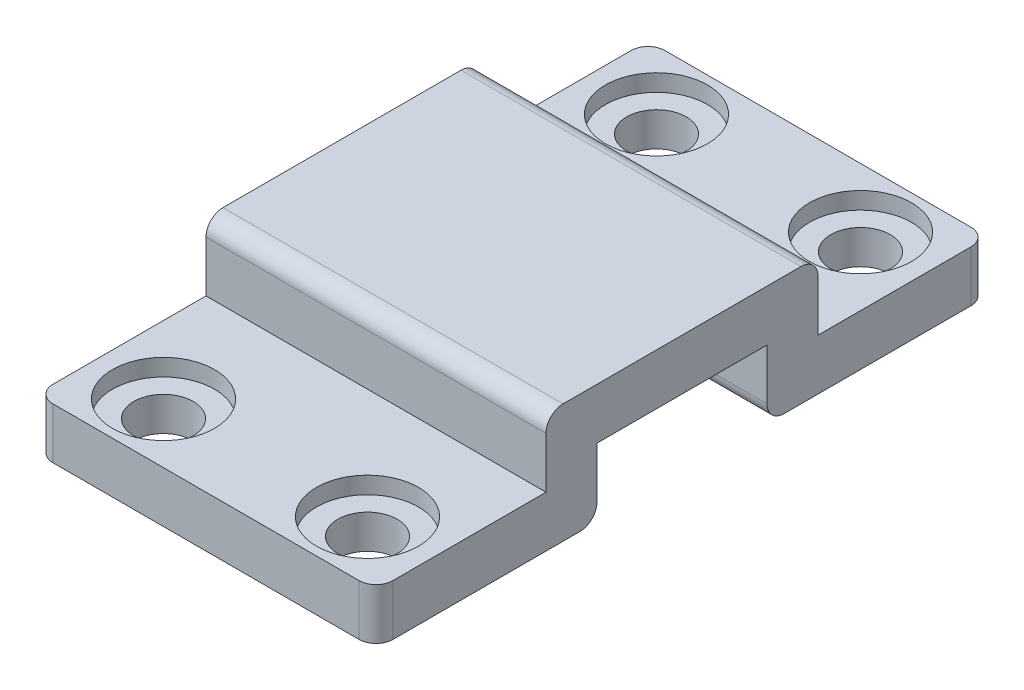
SolidWorks part; units mm, degrees
ref_plane "前视基准面" through (0, 0, 0) normal (0, 0, 1) x (1, 0, 0)
ref_plane "上视基准面" through (0, 0, 0) normal (0, 1, 0) x (1, 0, 0)
ref_plane "右视基准面" through (0, 0, 0) normal (1, 0, 0) x (0, 0, -1)
sketch "草图21" plane through (0, 0, 0) normal (0, 1, 0) x (1, 0, 0)
  line L1 (-10, -5) -> (10, -5)
  line L2 (-10, -5) -> (-10, 5)
  line L3 (-10, 5) -> (10, 5)
  line L4 (10, -5) -> (10, 5)
  line L5 (-10, -5) -> (10, 5) construction
  line L6 (-10, 5) -> (10, -5) construction
  point P0 (0, 0)
  dimension "D1" = 20
  dimension "D2" = 10
extrude "凸台-拉伸3" add sketch "草图21" along normal blind 3
sketch "草图22" plane through (0, 3, 0) normal (0, 1, 0) x (1, 0, 0)
  line L0 (-10, 0) -> (10, 0) construction
  line L1 (-10, -8) -> (10, -8)
  line L2 (-10, -8) -> (-10, -5)
  line L3 (-10, -5) -> (10, -5)
  line L4 (10, -8) -> (10, -5)
  line L5 (-10, -8) -> (10, -5) construction
  line L6 (-10, -5) -> (10, -8) construction
  line L7 (-10, 5) -> (-10, -5) construction
  line L8 (10, -5) -> (10, 5) construction
  line L9 (-10, 5) -> (10, 8) construction
  line L10 (-10, 8) -> (10, 5) construction
  line L11 (10, 8) -> (10, 5)
  line L12 (-10, 5) -> (10, 5)
  line L13 (-10, 8) -> (-10, 5)
  line L14 (-10, 8) -> (10, 8)
  point P0 (0, -6.5)
  point P16 (0, 6.5)
  dimension "D1" = 3
extrude "凸台-拉伸4" add sketch "草图22" against normal blind 7
sketch "草图23" plane through (0, 0, 8) normal (0, 0, 1) x (1, 0, 0)
  line L1 (-10, -1) -> (10, -1)
  line L2 (-10, -1) -> (-10, -4)
  line L3 (-10, -4) -> (10, -4)
  line L4 (10, -1) -> (10, -4)
  line L5 (-10, -1) -> (10, -4) construction
  line L6 (-10, -4) -> (10, -1) construction
  point P0 (0, -2.5)
  dimension "D1" = 3
extrude "凸台-拉伸5" add sketch "草图23" along normal blind 10
sketch "草图24" plane through (0, 0, -8) normal (0, 0, -1) x (-1, 0, 0)
  line L1 (-10, -1) -> (10, -1)
  line L2 (-10, -1) -> (-10, -4)
  line L3 (-10, -4) -> (10, -4)
  line L4 (10, -1) -> (10, -4)
  line L5 (-10, -1) -> (10, -4) construction
  line L6 (-10, -4) -> (10, -1) construction
  point P0 (0, -2.5)
  dimension "D1" = 3
extrude "凸台-拉伸6" add sketch "草图24" along normal blind 10
sketch "草图25" plane through (0, -1, 0) normal (0, 1, 0) x (1, 0, 0)
  line L0 (-10, 11) -> (10, 11) construction
  line L1 (-10, 18) -> (-10, 8) construction
  line L2 (10, 18) -> (10, 8) construction
  line L3 (10, 8) -> (-10, 8) construction
  line L4 (-10, 18) -> (-10, 11) construction
  line L5 (-10, 14.5) -> (10, 14.5) construction
  line L6 (0, 18) -> (0, -18) construction
  line L7 (-10, 18) -> (10, 18) construction
  line L8 (10, -18) -> (-10, -18) construction
  line L9 (-10, 0) -> (10, 0) construction
  line L10 (-10, 8) -> (-10, -8) construction
  line L11 (10, -8) -> (10, 8) construction
  circle A0 centre (-6, 14.5) radius 1.75
  circle A1 centre (-6, 14.5) radius 3
  circle A2 centre (6, 14.5) radius 3
  circle A3 centre (6, 14.5) radius 1.75
  circle A4 centre (6, -14.5) radius 1.75
  circle A5 centre (6, -14.5) radius 3
  circle A6 centre (-6, -14.5) radius 3
  circle A7 centre (-6, -14.5) radius 1.75
  dimension "D2" = 3.5
  dimension "D3" = 6
  dimension "D1" = 3
  dimension "D4" = 4
extrude "切除-拉伸1" cut sketch "草图25" against normal through all contours A0 | A3 | A7 | A4
sketch "草图26" plane through (0, -1, 0) normal (0, 1, 0) x (1, 0, 0)
  circle A1 centre (-6, 14.5) radius 3
  circle A2 centre (-6, 14.5) radius 3
  circle A3 centre (-6, 14.5) radius 1.75
  circle A4 centre (-6, 14.5) radius 1.75
  circle A5 centre (6, -14.5) radius 1.75
  circle A6 centre (6, -14.5) radius 1.75
  circle A7 centre (6, 14.5) radius 1.75
  circle A8 centre (6, 14.5) radius 1.75
  circle A9 centre (6, 14.5) radius 3
  circle A10 centre (6, 14.5) radius 3
  circle A11 centre (-6, -14.5) radius 1.75
  circle A12 centre (-6, -14.5) radius 1.75
  circle A13 centre (-6, -14.5) radius 3
  circle A14 centre (-6, -14.5) radius 3
  circle A15 centre (6, -14.5) radius 3
  circle A16 centre (6, -14.5) radius 3
  circle M13 centre (-6, 14.5) radius 1.75
  circle M14 centre (6, 14.5) radius 1.75
  dimension "D1" = 0
  dimension "D2" = 0
  dimension "D3" = 0
  dimension "D4" = 0
  dimension "D5" = 0
  dimension "D6" = 0
  dimension "D7" = 0
  dimension "D8" = 0
extrude "切除-拉伸2" cut sketch "草图26" against normal blind 1 contours A2 M13 | A10 M14 | A14 A12 | A16 A6
fillet "圆角1" radius 1 8 edges at (10, -2.5, 18) (-10, -2.5, 18) (-10, -2.5, -18) (10, -2.5, -18) (0, 3, 8) (0, 3, -8) (0, -4, 5) (0, -4, -5)
